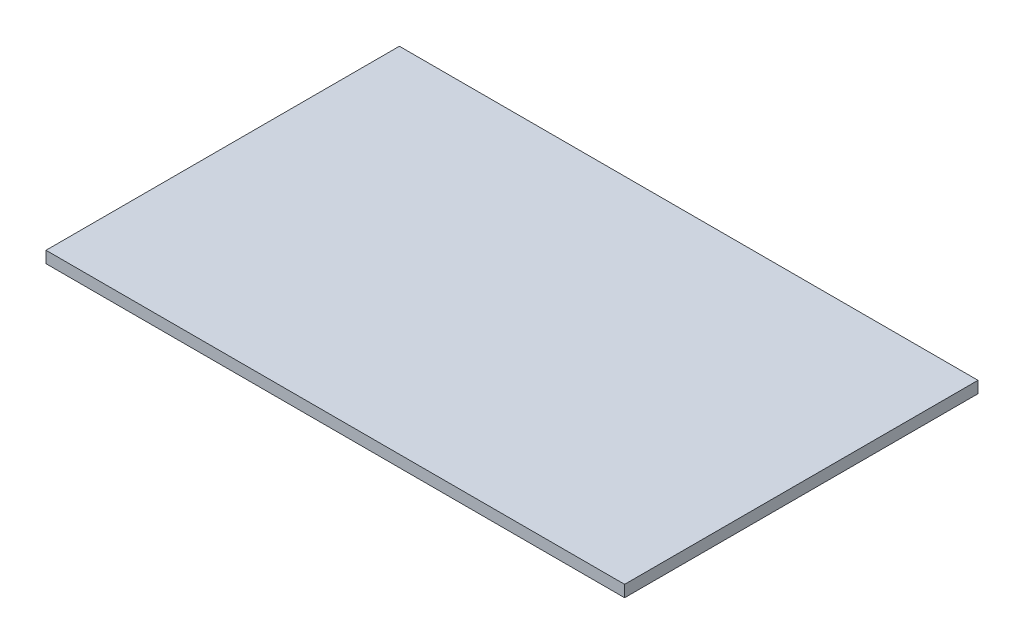
SolidWorks part; units mm, degrees
ref_plane "Front Plane" through (0, 0, 0) normal (0, 0, 1) x (1, 0, 0)
ref_plane "Top Plane" through (0, 0, 0) normal (0, 1, 0) x (1, 0, 0)
ref_plane "Right Plane" through (0, 0, 0) normal (1, 0, 0) x (0, 0, -1)
sketch "Sketch1" plane through (0, 0, 0) normal (0, 1, 0) x (1, 0, 0)
  line L1 (0, 0) -> (946.15, 0)
  line L2 (0, 0) -> (0, 577.85)
  line L3 (0, 577.85) -> (946.15, 577.85)
  line L4 (946.15, 0) -> (946.15, 577.85)
  dimension "D1" = 577.85
  dimension "D2" = 946.15
extrude "Boss-Extrude1" add sketch "Sketch1" along normal blind 19.05
